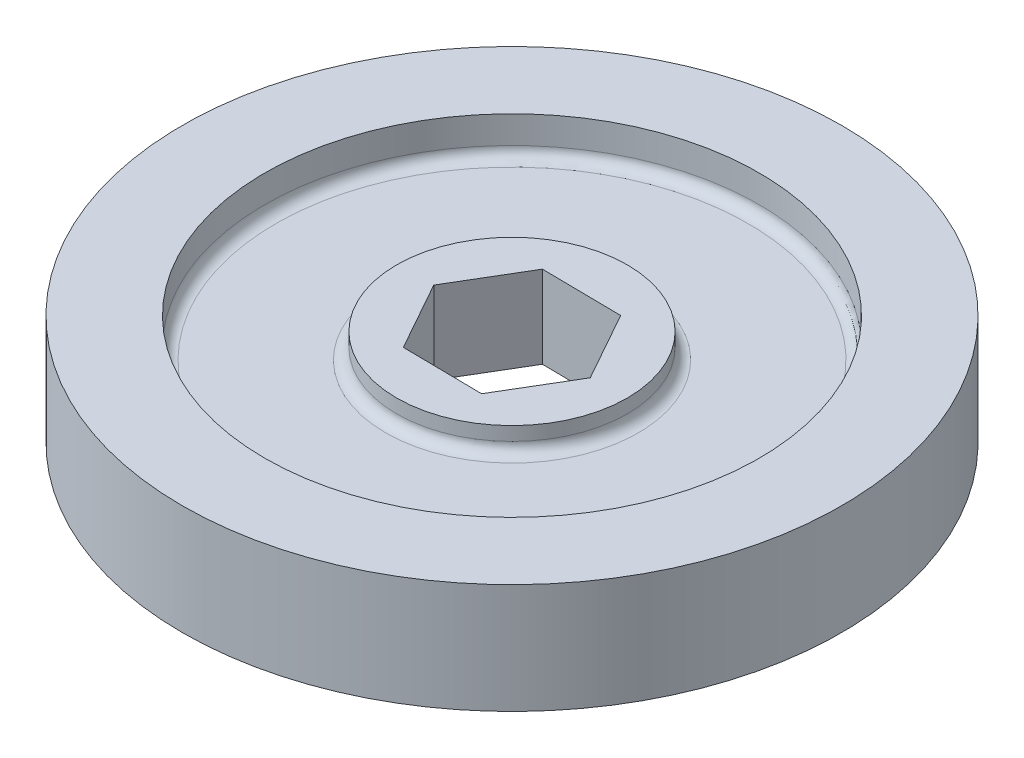
SolidWorks part; units mm, degrees
ref_plane "Front Plane" through (0, 0, 0) normal (0, 0, 1) x (1, 0, 0)
ref_plane "Top Plane" through (0, 0, 0) normal (0, 1, 0) x (1, 0, 0)
ref_plane "Right Plane" through (0, 0, 0) normal (1, 0, 0) x (0, 0, -1)
sketch "Sketch1" plane through (0, 0, 0) normal (0, 1, 0) x (1, 0, 0)
  circle A0 centre (0, 0) radius 30
  dimension "D1" = 60
extrude "Boss-Extrude1" add sketch "Sketch1" along normal blind 10
sketch "Sketch2" plane through (0, 10, 0) normal (0, 1, 0) x (1, 0, 0)
  circle A0 centre (0, 0) radius 22.5
  circle A1 centre (0, 0) radius 30 construction
  dimension "D1" = 7.5
extrude "Cut-Extrude1" cut sketch "Sketch2" against normal blind 3.5
sketch "Sketch3" plane through (0, 0, 0) normal (0, -1, 0) x (1, 0, 0)
  circle A0 centre (0, 0) radius 22.5
  circle A1 centre (0, 0) radius 30 construction
  dimension "D1" = 7.5
extrude "Cut-Extrude2" cut sketch "Sketch3" against normal blind 3.5
sketch "Sketch5" plane through (0, 6.5, 0) normal (0, 1, 0) x (1, 0, 0)
  circle A0 centre (0, 0) radius 10.5
  dimension "D1" = 21
extrude "Boss-Extrude2" add sketch "Sketch5" along normal blind 2.25
sketch "Sketch6" plane through (0, 3.5, 0) normal (0, -1, 0) x (1, 0, 0)
  circle A0 centre (0, 0) radius 10.5
  dimension "D1" = 21
extrude "Boss-Extrude3" add sketch "Sketch6" along normal blind 2.25
sketch "Sketch4" plane through (0, 6.5, 0) normal (0, 1, 0) x (1, 0, 0)
  line L1 (3.6896, 6.2024) -> (-3.5266, 6.2965)
  line L2 (-3.5266, 6.2965) -> (-7.2163, 0.0941)
  line L3 (-7.2163, 0.0941) -> (-3.6896, -6.2024)
  line L4 (-3.6896, -6.2024) -> (3.5266, -6.2965)
  line L5 (3.5266, -6.2965) -> (7.2163, -0.0941)
  line L6 (7.2163, -0.0941) -> (3.6896, 6.2024)
  circle A0 centre (0, 0) radius 6.25 construction
  dimension "D1" = 12.5
extrude "Cut-Extrude3" cut sketch "Sketch4" against normal through all both and the other way through all
fillet "Fillet1" radius 1 2 edges at (0, 3.5, -22.5) (0, 6.5, 22.5)
fillet "Fillet2" radius 1 2 edges at (0, 3.5, -10.5) (0, 6.5, 10.5)
